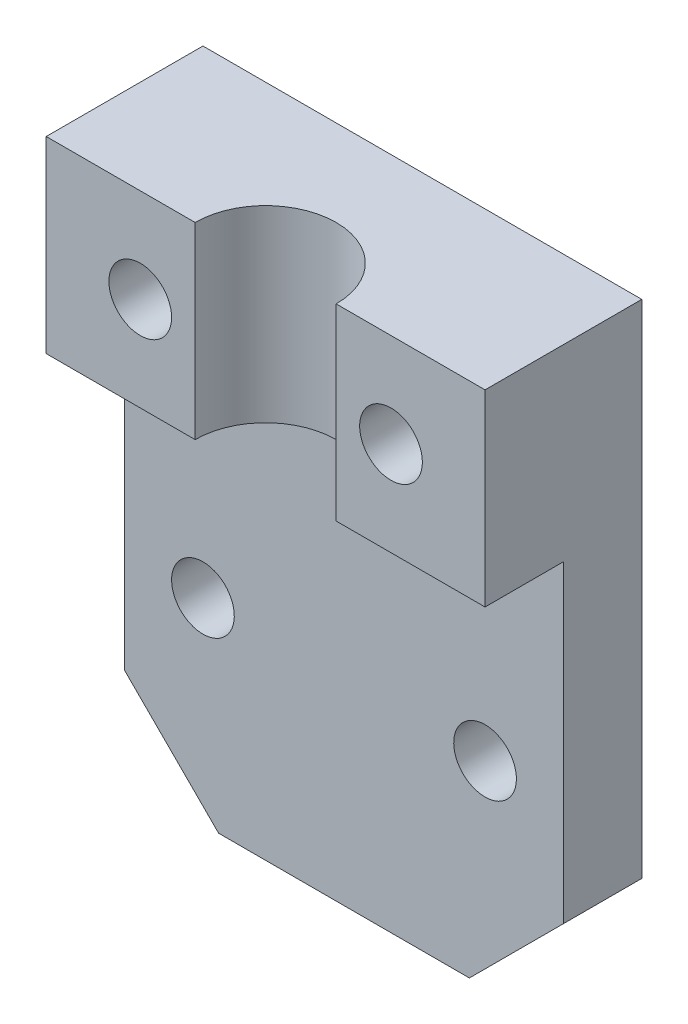
SolidWorks part; units mm, degrees
ref_plane "前视基准面" through (0, 0, 0) normal (0, 0, 1) x (1, 0, 0)
ref_plane "上视基准面" through (0, 0, 0) normal (0, 1, 0) x (1, 0, 0)
ref_plane "右视基准面" through (0, 0, 0) normal (1, 0, 0) x (0, 0, -1)
sketch "草图1" plane through (0, 0, 0) normal (0, 0, 1) x (1, 0, 0)
  line L48 (1262.2609, 1015.6126) -> (1268.7609, 1015.6126) construction
  line L49 (1265.5109, 1012.6126) -> (1265.5109, 1018.6126) construction
  line L50 (1249.5109, 1012.6126) -> (1249.5109, 1018.6126) construction
  line L51 (1252.7609, 1015.6126) -> (1246.2609, 1015.6126) construction
  line L52 (1243.5109, 989.6126) -> (1243.5109, 1021.6126)
  line L53 (1249.5109, 983.6126) -> (1243.5109, 989.6126)
  line L56 (1271.5109, 989.6126) -> (1271.5109, 1021.6126)
  line L57 (1265.5109, 983.6126) -> (1271.5109, 989.6126)
  line L58 (1249.5109, 983.6126) -> (1265.5109, 983.6126)
  line L59 (1243.5109, 1021.6126) -> (1271.5109, 1021.6126)
  line L77 (1257.5109, 980.0476) -> (1257.5109, 1025.9686) construction
  line L95 (1262.3075, 996.1126) -> (1270.3848, 996.1126) construction
  line L96 (1266.5109, 999.5711) -> (1266.5109, 992.3452) construction
  line L97 (1244.3075, 996.1126) -> (1252.3848, 996.1126) construction
  line L98 (1248.5109, 999.5711) -> (1248.5109, 992.3452) construction
  circle A6 centre (1265.5109, 1015.6126) radius 2
  circle A7 centre (1249.5109, 1015.6126) radius 2
  circle A10 centre (1248.5109, 996.1126) radius 2
  circle A12 centre (1266.5109, 996.1126) radius 2
extrude "拉伸1" add sketch "草图1" along normal blind 10
sketch "草图2" plane through (1243.5109, 0, 0) normal (-1, 0, 0) x (0, 0, 1)
  line L0 (11.5058, 1009.6126) -> (5, 1009.6126)
  line L1 (5, 1009.6126) -> (5, 976.2556)
  line L2 (5, 976.2556) -> (11.5058, 976.2556)
  line L4 (10, 1021.6126) -> (0, 1021.6126) construction
  line L5 (10, 1021.6126) -> (10, 989.6126) construction
  line L7 (11.5058, 1009.6126) -> (11.5058, 976.2556)
  dimension "D1" = 12
  dimension "D2" = 33.3571
  dimension "D3" = 5
extrude "拉伸2" cut sketch "草图2" against normal up to next
sketch "草图3" plane through (0, 1021.6126, 0) normal (0, 1, 0) x (1, 0, 0)
  line L0 (1257.5109, 0) -> (1257.5109, -10) construction
  line L1 (1271.5109, 0) -> (1243.5109, 0) construction
  line L2 (1271.5109, -10) -> (1243.5109, -10) construction
  line L3 (1257.5109, -10) -> (1257.5109, -12.4983) construction
  circle A0 centre (1257.5109, -10) radius 4.5
extrude "拉伸3" cut sketch "草图3" against normal blind 20
